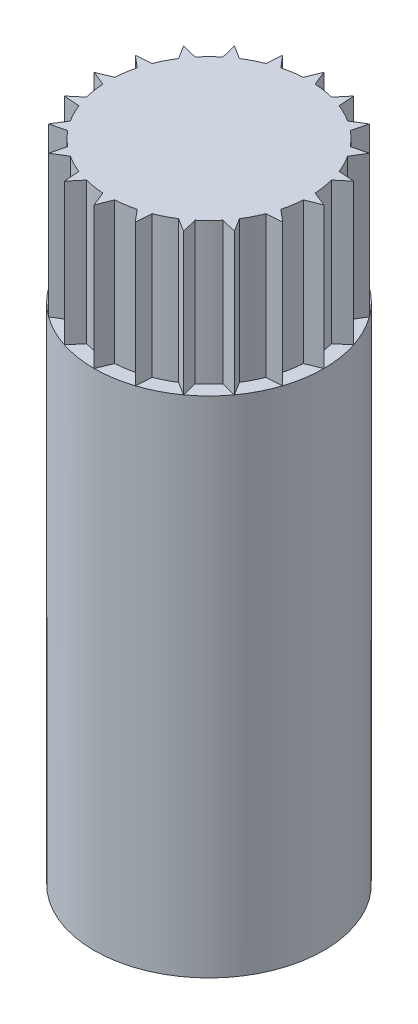
SolidWorks part; units mm, degrees
material "ABS"
ref_plane "Front Plane" through (0, 0, 0) normal (0, 0, 1) x (1, 0, 0)
ref_plane "Top Plane" through (0, 0, 0) normal (0, 1, 0) x (1, 0, 0)
ref_plane "Right Plane" through (0, 0, 0) normal (1, 0, 0) x (0, 0, -1)
sketch "Sketch1" plane through (0, 0, 0) normal (0, 1, 0) x (1, 0, 0)
  circle A0 centre (0, 0) radius 4.86
  dimension "D1" = 9.72
extrude "Boss-Extrude1" add sketch "Sketch1" along normal blind 21.336
sketch "Sketch2" plane through (0, 21.336, 0) normal (0, 1, 0) x (1, 0, 0)
  line L0 (0, 4.86) -> (0.2508, 4.2426)
  line L2 (0, 4.86) -> (-0.2508, 4.2426)
  line L3 (1.5018, 4.6221) -> (1.5495, 3.9575)
  line L4 (1.5018, 4.6221) -> (1.0726, 4.1124)
  line L5 (2.8566, 3.9318) -> (2.6966, 3.2849)
  line L6 (2.8566, 3.9318) -> (2.2909, 3.5797)
  line L7 (3.9318, 2.8566) -> (3.5797, 2.2909)
  line L8 (3.9318, 2.8566) -> (3.2849, 2.6966)
  line L9 (4.6221, 1.5018) -> (4.1124, 1.0726)
  line L10 (4.6221, 1.5018) -> (3.9575, 1.5495)
  line L11 (4.86, 0) -> (4.2426, -0.2508)
  line L12 (4.86, 0) -> (4.2426, 0.2508)
  line L13 (4.6221, -1.5018) -> (3.9575, -1.5495)
  line L14 (4.6221, -1.5018) -> (4.1124, -1.0726)
  line L15 (3.9318, -2.8566) -> (3.2849, -2.6966)
  line L16 (3.9318, -2.8566) -> (3.5797, -2.2909)
  line L17 (2.8566, -3.9318) -> (2.2909, -3.5797)
  line L18 (2.8566, -3.9318) -> (2.6966, -3.2849)
  line L19 (1.5018, -4.6221) -> (1.0726, -4.1124)
  line L20 (1.5018, -4.6221) -> (1.5495, -3.9575)
  line L21 (0, -4.86) -> (-0.2508, -4.2426)
  line L22 (0, -4.86) -> (0.2508, -4.2426)
  line L23 (-1.5018, -4.6221) -> (-1.5495, -3.9575)
  line L24 (-1.5018, -4.6221) -> (-1.0726, -4.1124)
  line L25 (-2.8566, -3.9318) -> (-2.6966, -3.2849)
  line L26 (-2.8566, -3.9318) -> (-2.2909, -3.5797)
  line L27 (-3.9318, -2.8566) -> (-3.5797, -2.2909)
  line L28 (-3.9318, -2.8566) -> (-3.2849, -2.6966)
  line L29 (-4.6221, -1.5018) -> (-4.1124, -1.0726)
  line L30 (-4.6221, -1.5018) -> (-3.9575, -1.5495)
  line L31 (-4.86, 0) -> (-4.2426, 0.2508)
  line L32 (-4.86, 0) -> (-4.2426, -0.2508)
  line L33 (-4.6221, 1.5018) -> (-3.9575, 1.5495)
  line L34 (-4.6221, 1.5018) -> (-4.1124, 1.0726)
  line L35 (-3.9318, 2.8566) -> (-3.2849, 2.6966)
  line L36 (-3.9318, 2.8566) -> (-3.5797, 2.2909)
  line L37 (-2.8566, 3.9318) -> (-2.2909, 3.5797)
  line L38 (-2.8566, 3.9318) -> (-2.6966, 3.2849)
  line L39 (-1.5018, 4.6221) -> (-1.0726, 4.1124)
  line L40 (-1.5018, 4.6221) -> (-1.5495, 3.9575)
  arc A0 (-1.5495, 3.9575) -> (-2.2909, 3.5797) centre (0, 0) ccw
  circle A1 centre (0, 0) radius 4.86 construction
  arc A2 (-0.2508, 4.2426) -> (-1.0726, 4.1124) centre (0, 0) ccw
  arc A3 (1.0726, 4.1124) -> (0.2508, 4.2426) centre (0, 0) ccw
  arc A4 (2.2909, 3.5797) -> (1.5495, 3.9575) centre (0, 0) ccw
  arc A5 (3.2849, 2.6966) -> (2.6966, 3.2849) centre (0, 0) ccw
  arc A6 (3.9575, 1.5495) -> (3.5797, 2.2909) centre (0, 0) ccw
  arc A7 (4.2426, 0.2508) -> (4.1124, 1.0726) centre (0, 0) ccw
  arc A8 (4.1124, -1.0726) -> (4.2426, -0.2508) centre (0, 0) ccw
  arc A9 (3.5797, -2.2909) -> (3.9575, -1.5495) centre (0, 0) ccw
  arc A10 (2.6966, -3.2849) -> (3.2849, -2.6966) centre (0, 0) ccw
  arc A11 (1.5495, -3.9575) -> (2.2909, -3.5797) centre (0, 0) ccw
  arc A12 (0.2508, -4.2426) -> (1.0726, -4.1124) centre (0, 0) ccw
  arc A13 (-1.0726, -4.1124) -> (-0.2508, -4.2426) centre (0, 0) ccw
  arc A14 (-2.2909, -3.5797) -> (-1.5495, -3.9575) centre (0, 0) ccw
  arc A15 (-3.2849, -2.6966) -> (-2.6966, -3.2849) centre (0, 0) ccw
  arc A16 (-3.9575, -1.5495) -> (-3.5797, -2.2909) centre (0, 0) ccw
  arc A17 (-4.2426, -0.2508) -> (-4.1124, -1.0726) centre (0, 0) ccw
  arc A18 (-4.1124, 1.0726) -> (-4.2426, 0.2508) centre (0, 0) ccw
  arc A19 (-3.5797, 2.2909) -> (-3.9575, 1.5495) centre (0, 0) ccw
  arc A20 (-2.6966, 3.2849) -> (-3.2849, 2.6966) centre (0, 0) ccw
  point P69 (0, 0)
  dimension "D1" = 8.5
  dimension "D2" = 20
extrude "Boss-Extrude2" add sketch "Sketch2" along normal blind 6
